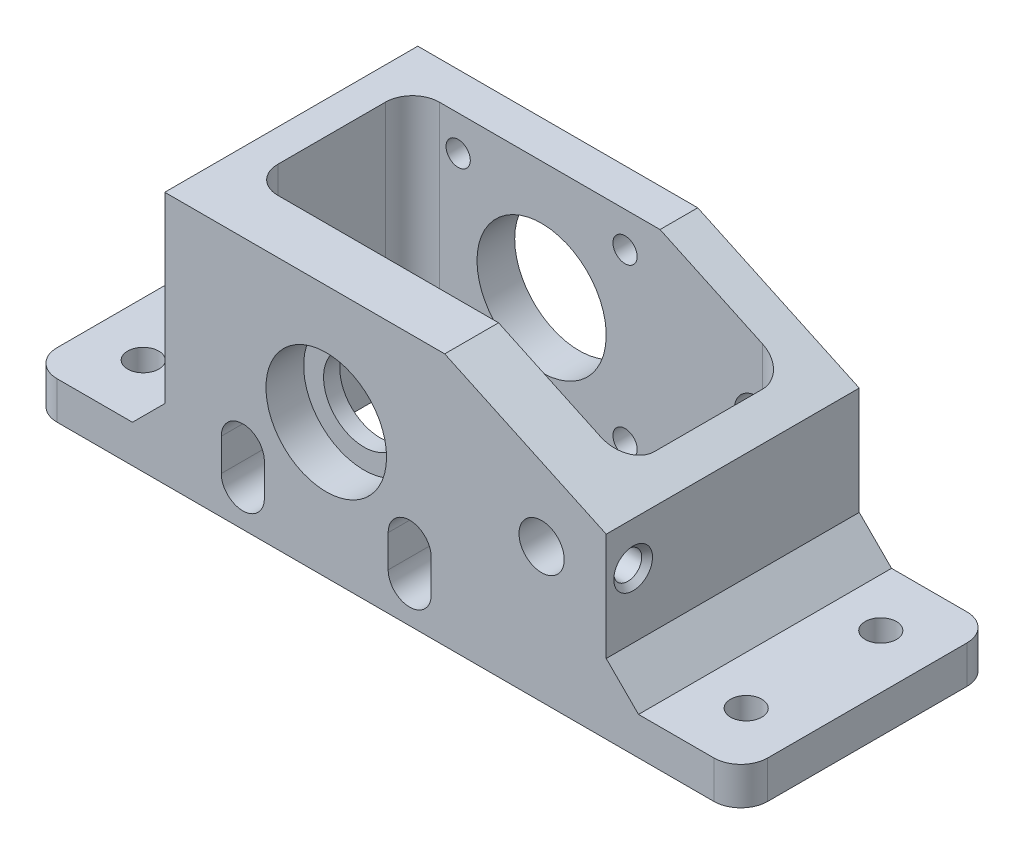
SolidWorks part; units mm, degrees
ref_plane "Front Plane" through (0, 0, 0) normal (0, 0, 1) x (1, 0, 0)
ref_plane "Top Plane" through (0, 0, 0) normal (0, 1, 0) x (1, 0, 0)
ref_plane "Right Plane" through (0, 0, 0) normal (1, 0, 0) x (0, 0, -1)
sketch "Sketch1" plane through (0, 0, 0) normal (0, 0, 1) x (1, 0, 0)
  line L0 (-30, -25) -> (-30, 22)
  line L1 (-30, 22) -> (22, 22)
  line L2 (22, 22) -> (52, 8)
  line L3 (52, 8) -> (52, -25)
  line L4 (52, -25) -> (-30, -25)
  circle A0 centre (0, 0) radius 7.5
  circle A1 centre (40, 0) radius 4.2
  dimension "D1" = 15
  dimension "D6" = 8.4
  dimension "D2" = 40
  dimension "D3" = 30
  dimension "D4" = 25
  dimension "D5" = 22
  dimension "D7" = 12
  dimension "D8" = 33
  dimension "D9" = 22
extrude "Boss-Extrude1" add sketch "Sketch1" along normal blind 47
sketch "Sketch2" plane through (0, 0, 47) normal (0, 0, 1) x (1, 0, 0)
  circle A0 centre (0, 0) radius 11.2
  dimension "D1" = 22.4
extrude "Cut-Extrude1" cut sketch "Sketch2" against normal blind 7
sketch "Sketch3" plane through (0, 0, 0) normal (0, 0, -1) x (-1, 0, 0)
  line L0 (-15.5, 15.5) -> (15.5, -15.5) construction
  circle A0 centre (-15.5, 15.5) radius 2.25
  circle A1 centre (-15.5, -15.5) radius 2.25
  circle A2 centre (15.5, -15.5) radius 2.25
  circle A3 centre (15.5, 15.5) radius 2.25
  circle A4 centre (0, 0) radius 12
  dimension "D1" = 4.5
  dimension "D4" = 24
  dimension "D2" = 31
  dimension "D3" = 31
extrude "Cut-Extrude2" cut sketch "Sketch3" against normal blind 15
sketch "Sketch4" plane through (0, 22, 0) normal (0, 1, 0) x (1, 0, 0)
  line L0 (22, 0) -> (-30, 0) construction
  line L1 (-19, -7) -> (41, -7)
  line L2 (-24, -12) -> (-24, -32)
  line L3 (-19, -37) -> (41, -37)
  line L4 (46, -12) -> (46, -32)
  line L5 (22, -47) -> (-30, -47) construction
  line L6 (-30, -47) -> (-30, 0) construction
  line L7 (52, -47) -> (52, 0) construction
  arc A0 (41, -37) -> (46, -32) centre (41, -32) ccw
  arc A1 (41, -7) -> (46, -12) centre (41, -12) cw
  arc A2 (-19, -7) -> (-24, -12) centre (-19, -12) ccw
  arc A3 (-24, -32) -> (-19, -37) centre (-19, -32) ccw
  dimension "D5" = 5
  dimension "D1" = 7
  dimension "D2" = 10
  dimension "D3" = 6
  dimension "D4" = 6
extrude "Cut-Extrude3" cut sketch "Sketch4" against normal through all
sketch "Sketch6" plane through (0, 0, 47) normal (0, 0, 1) x (1, 0, 0)
  line L0 (-30, -25) -> (52, -25) construction
  line L2 (-19.5, -12) -> (-19.5, -18)
  line L3 (-11.5, -12) -> (-11.5, -18)
  line L4 (11.5, -12) -> (11.5, -18)
  line L5 (19.5, -12) -> (19.5, -18)
  arc A0 (-11.5, -12) -> (-19.5, -12) centre (-15.5, -12) ccw
  arc A1 (19.5, -12) -> (11.5, -12) centre (15.5, -12) ccw
  arc A3 (-19.5, -18) -> (-11.5, -18) centre (-15.5, -18) ccw
  arc A4 (11.5, -18) -> (19.5, -18) centre (15.5, -18) ccw
  dimension "D1" = 8
  dimension "D2" = 15.5
  dimension "D3" = 13
  dimension "D4" = 15.5
  dimension "D5" = 7
extrude "Cut-Extrude4" cut sketch "Sketch6" against normal blind 20
sketch "Sketch7" plane through (52, 0, 0) normal (1, 0, 0) x (0, 0, -1)
  line L0 (-47, -25) -> (-47, 8) construction
  circle A0 centre (-42, 0) radius 2.6
  dimension "D1" = 5.2
  dimension "D2" = 5
extrude "Cut-Extrude5" cut sketch "Sketch7" against normal blind 10
chamfer "Chamfer2" distance 1 angle 45 1 edges at (52, 2.6, 42)
sketch "Sketch9" plane through (0, -25, 0) normal (0, -1, 0) x (1, 0, 0)
  line L0 (-30, 0) -> (52, 0) construction
  line L1 (-30, 47) -> (-55, 47)
  line L2 (-30, 47) -> (-30, 0)
  line L3 (-30, 0) -> (-55, 0)
  line L4 (-55, 47) -> (-55, 0)
  line L5 (52, 47) -> (77, 47)
  line L6 (52, 47) -> (52, 0)
  line L7 (52, 0) -> (77, 0)
  line L8 (77, 47) -> (77, 0)
  line L9 (-30, 47) -> (52, 47) construction
  dimension "D1" = 47
  dimension "D2" = 25
extrude "Boss-Extrude2" add sketch "Sketch9" against normal blind 7 separate body
hole_wizard "M5 Clearance Hole1" positions "Sketch11" profile "Sketch10" hole size "M5" standard "ANSI Metric" end condition through all
sketch "Sketch11" plane through (0, -18, 0) normal (0, 1, 0) x (1, 0, 0)
  line L0 (67, -36) -> (-45, -36) construction
  line L1 (-45, -36) -> (-45, -11) construction
  line L2 (-45, -11) -> (67, -11) construction
  line L3 (67, -11) -> (67, -36) construction
  line L5 (77, -47) -> (52, -47) construction
  line L6 (77, 0) -> (77, -47) construction
  line L7 (-55, -47) -> (-55, 0) construction
  line L10 (52, 0) -> (77, 0) construction
  point P0 (-45, -36)
  point P3 (-45, -11)
  point P5 (67, -11)
  point P7 (67, -36)
  point P18 (64.5, -47)
  dimension "D1" = 25
  dimension "D2" = 11
  dimension "D3" = 10
  dimension "D4" = 10
  dimension "D5" = 112
  dimension "D6" = 11
sketch "Sketch10" plane through (-45, -18, 36) normal (1, 0, 0) x (0, 0, 1)
  line L0 (0, 0) -> (0, 7)
  line L1 (0, 7) -> (2.9, 7)
  line L2 (2.9, 7) -> (2.9, 0)
  line L5 (2.9, 0) -> (0, 0)
  line L11 (0, -6.35) -> (0, 107.95) construction
  dimension "Thru Hole Dia." = 5.8
  dimension "Thru Hole Depth" = 7
sketch "Sketch13" plane through (0, 0, 0) normal (0, 0, -1) x (-1, 0, 0)
  line L0 (-52, -18) -> (-58, -18)
  line L1 (-52, -18) -> (-77, -18) construction
  line L2 (-58, -18) -> (-52, -12)
  line L3 (-52, -25) -> (-52, 8) construction
  line L4 (-52, -12) -> (-52, -18)
  line L5 (30, -18) -> (30, -12)
  line L6 (30, 22) -> (30, -25) construction
  line L7 (30, -12) -> (36, -18)
  line L8 (55, -18) -> (30, -18) construction
  line L9 (36, -18) -> (30, -18)
  dimension "D1" = 6
  dimension "D2" = 6
extrude "Boss-Extrude3" add sketch "Sketch13" against normal up to surface (47 mm away) up to face at (64.5, -21.5, 47)
fillet "Fillet1" radius 5 4 edges at (-55, -21.5, 47) (-55, -21.5, 0) (77, -21.5, 0) (77, -21.5, 47)
